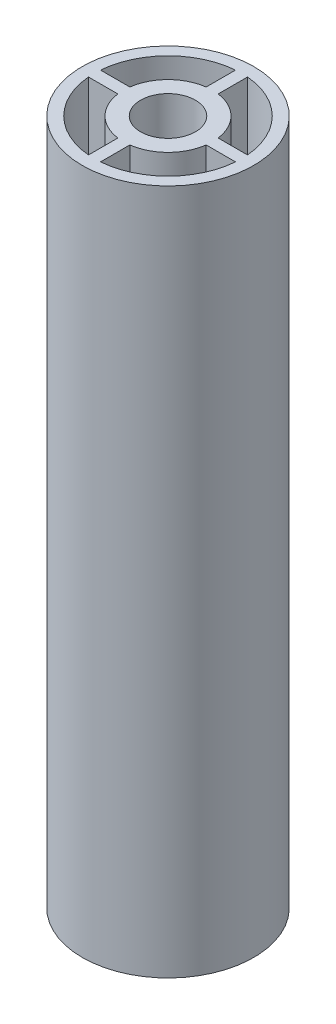
SolidWorks part; units mm, degrees
ref_plane "前视基准面" through (0, 0, 0) normal (0, 0, 1) x (1, 0, 0)
ref_plane "上视基准面" through (0, 0, 0) normal (0, 1, 0) x (1, 0, 0)
ref_plane "右视基准面" through (0, 0, 0) normal (1, 0, 0) x (0, 0, -1)
sketch "草图1" plane through (0, 0, 0) normal (0, 1, 0) x (1, 0, 0)
  line L0 (2.5763, 0.35) -> (4.2857, 0.35)
  line L1 (5, 0.35) -> (5, -0.35)
  line L2 (5, -0.35) -> (4.9877, -0.35)
  line L3 (0, 0) -> (4.3, 0) construction
  line L4 (-0.35, -5) -> (-0.35, -4.9877)
  line L5 (0.35, -5) -> (-0.35, -5)
  line L6 (0.35, -2.5763) -> (0.35, -4.2857)
  line L7 (-5, 0.35) -> (-4.9877, 0.35)
  line L8 (-5, -0.35) -> (-5, 0.35)
  line L9 (-2.5763, -0.35) -> (-4.2857, -0.35)
  line L10 (0.35, 5) -> (0.35, 4.9877)
  line L11 (-0.35, 5) -> (0.35, 5)
  line L12 (-0.35, 2.5763) -> (-0.35, 4.2857)
  line L13 (0.35, 4.2857) -> (0.35, 2.5763)
  line L14 (-0.35, 4.9877) -> (-0.35, 5)
  line L15 (-4.2857, 0.35) -> (-2.5763, 0.35)
  line L16 (-4.9877, -0.35) -> (-5, -0.35)
  line L17 (-0.35, -4.2857) -> (-0.35, -2.5763)
  line L18 (0.35, -4.9877) -> (0.35, -5)
  line L19 (4.9877, 0.35) -> (5, 0.35)
  line L20 (5, 0) -> (7.6079, 0) construction
  line L21 (4.2857, -0.35) -> (2.5763, -0.35)
  circle A0 centre (0, 0) radius 1.6
  arc A1 (-0.35, 2.5763) -> (-2.5763, 0.35) centre (0, 0) ccw
  arc A2 (-2.5763, -0.35) -> (-0.35, -2.5763) centre (0, 0) ccw
  arc A3 (0.35, -2.5763) -> (2.5763, -0.35) centre (0, 0) ccw
  arc A4 (2.5763, 0.35) -> (0.35, 2.5763) centre (0, 0) ccw
  circle A5 centre (0, 0) radius 5
  arc A6 (-0.35, 4.2857) -> (-4.2857, 0.35) centre (0, 0) ccw
  arc A7 (-4.2857, -0.35) -> (-0.35, -4.2857) centre (0, 0) ccw
  arc A8 (0.35, -4.2857) -> (4.2857, -0.35) centre (0, 0) ccw
  arc A9 (4.2857, 0.35) -> (0.35, 4.2857) centre (0, 0) ccw
  point P24 (0, 0)
  dimension "D1" = 3.2
  dimension "D2" = 1
  dimension "D6" = 0.7
  dimension "D3" = 0.7
  dimension "D4" = 5
  dimension "D5" = 4
extrude "凸台-拉伸1" add sketch "草图1" along normal blind 40 contours A5 A9 L0 A4 L13 A8 L6 A3 L21 A7 L9 A2 L17 A6 L12 A1 L15 A0
